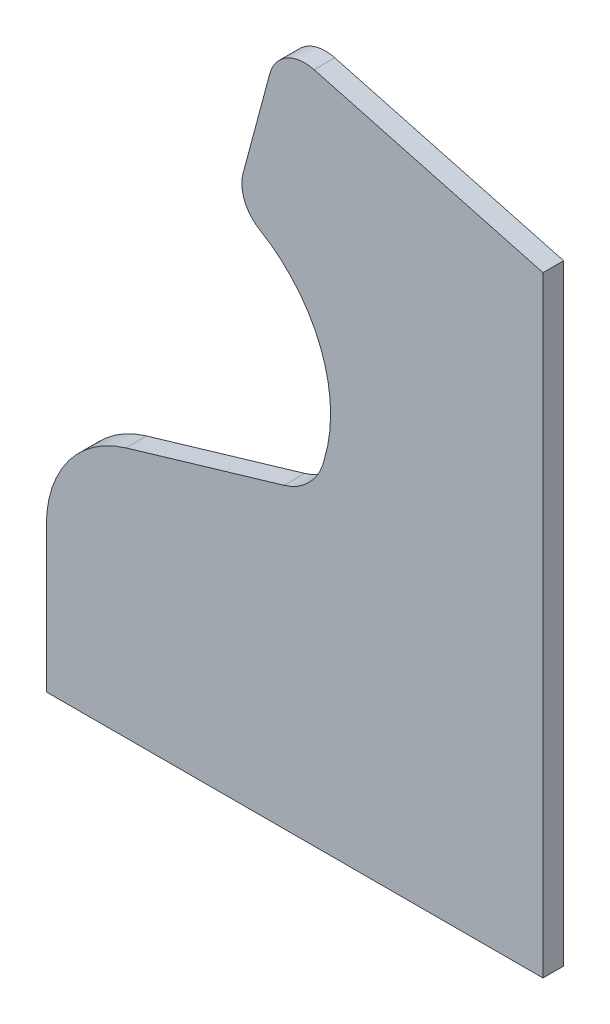
SolidWorks part; units mm, degrees
ref_plane "Alzado" through (0, 0, 0) normal (0, 0, 1) x (1, 0, 0)
ref_plane "Planta" through (0, 0, 0) normal (0, 1, 0) x (1, 0, 0)
ref_plane "Vista lateral" through (0, 0, 0) normal (1, 0, 0) x (0, 0, -1)
sketch "Croquis1" plane through (0, 0, 0) normal (0, 0, 1) x (1, 0, 0)
  line L0 (0, 0) -> (2.3, 0)
  line L1 (0, 0) -> (2.3, 0)
  line L2 (0, 0) -> (2.3, 0) construction
  line L3 (-0.6654, -0.3038) -> (30, -0.2651) construction
  line L4 (0, 0) -> (2.3, 0) construction
  line L5 (30, -0.2651) -> (30, 99.7349) construction
  line L11 (37.916, 121.4216) -> (114.5378, 144.0253)
  line L12 (0, 0) -> (2.3, 0) construction
  line L15 (0, 0) -> (2.3, 0) construction
  line L17 (0, 0) -> (2.3, 0) construction
  line L20 (240, 120.0567) -> (241.4638, 120.0567) construction
  line L30 (94.6659, 265.0261) -> (107.6068, 313.3223) construction
  line L34 (94.6659, 265.0261) -> (107.6068, 313.3223)
  line L35 (240, 0) -> (240, 296)
  line L36 (129.0812, 325.7206) -> (240, 296)
  line L37 (-0.6654, 69.8147) -> (-0.6654, -0.3038)
  line L38 (240, 0) -> (-0.6654, -0.3038)
  line L40 (37.916, 121.4216) -> (114.5378, 144.0253) construction
  arc A4 (37.916, 121.4216) -> (-0.6654, 69.8147) centre (53.1402, 69.8147) ccw
  arc A7 (134.1217, 165.008) -> (102.6824, 245.3926) centre (67.0696, 185.1236) ccw
  arc A8 (114.5378, 144.0253) -> (134.1217, 165.008) centre (106.5465, 171.1144) ccw
  arc A10 (94.6659, 265.0261) -> (102.6824, 245.3926) centre (111.6022, 260.488) ccw
  arc A11 (129.0812, 325.7206) -> (107.6068, 313.3223) centre (124.5431, 308.7843) ccw
extrude "Saliente-Extruir1" add sketch "Croquis1" along normal blind 10
